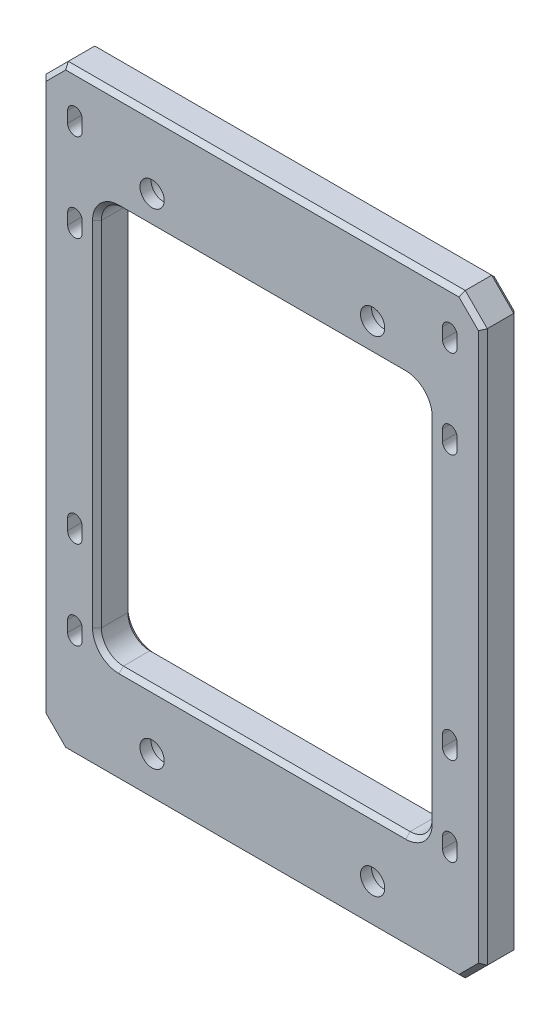
SolidWorks part; units mm, degrees
ref_plane "前视基准面" through (0, 0, 0) normal (0, 0, 1) x (1, 0, 0)
ref_plane "上视基准面" through (0, 0, 0) normal (0, 1, 0) x (1, 0, 0)
ref_plane "右视基准面" through (0, 0, 0) normal (1, 0, 0) x (0, 0, -1)
sketch "草图1" plane through (0, 0, 0) normal (0, 0, 1) x (1, 0, 0)
  line L1 (-100, 135) -> (100, 135)
  line L2 (-100, 135) -> (-100, -135)
  line L3 (-100, -135) -> (100, -135)
  line L4 (100, 135) -> (100, -135)
  line L5 (-100, 135) -> (100, -135) construction
  line L6 (-100, -135) -> (100, 135) construction
  point P0 (0, 0)
  dimension "D1" = 270
  dimension "D2" = 200
extrude "凸台-拉伸1" add sketch "草图1" along normal blind 16
hole_wizard "打孔尺寸(%根据)内六角圆柱头螺钉的类型1" positions "草图2" profile "草图3" counterbore size "M10" standard "GB" end condition through all
sketch "草图2" plane through (0, 0, 0) normal (0, 0, -1) x (-1, 0, 0)
  point P0 (-50, -116)
  point P2 (50, -116)
  point P4 (-50, 104)
  point P6 (50, 104)
sketch "草图3" plane through (50, -116, 0) normal (1, 0, 0) x (0, 1, 0)
  line L0 (0, 0) -> (0, 16)
  line L1 (0, 16) -> (5.5, 16)
  line L3 (5.5, 16) -> (5.5, 11)
  line L4 (5.5, 11) -> (9, 11)
  line L5 (9, 11) -> (9, 0)
  line L7 (9, 0) -> (0, 0)
  line L11 (0, -6.35) -> (0, 107.95) construction
  dimension "通孔孔直径" = 11
  dimension "通孔孔深度" = 16
  dimension "柱形沉头孔直径" = 18
  dimension "柱形沉头孔深度" = 11
sketch "草图4" plane through (0, 0, 16) normal (0, 0, 1) x (1, 0, 0)
  line L8 (100, -40.9) -> (-100, -40.9) construction
  line L9 (100, -80.9) -> (-100, -80.9) construction
  line L10 (100, -89.1) -> (-100, -89.1) construction
  line L11 (100, -49.1) -> (-100, -49.1) construction
  line L12 (100, 79.1) -> (-100, 79.1) construction
  line L13 (100, 70.9) -> (-100, 70.9) construction
  line L14 (100, 110.9) -> (-100, 110.9) construction
  line L15 (100, 119.1) -> (-100, 119.1) construction
  line L16 (100, -135) -> (100, 135) construction
  line L17 (-100, 135) -> (-100, -135) construction
  line L18 (100, -135) -> (100, 135) construction
  line L19 (-100, 135) -> (-100, -135) construction
  line L20 (0, 119.1) -> (0, 110.9) construction
  line L21 (0, 79.1) -> (0, 70.9) construction
  line L22 (0, -40.9) -> (0, -49.1) construction
  line L23 (0, -80.9) -> (0, -89.1) construction
  line L24 (-85, 115) -> (85, 115) construction
  line L25 (-85, 75) -> (85, 75) construction
  line L26 (-85, -45) -> (85, -45) construction
  line L27 (-85, -85) -> (85, -85) construction
  line L28 (-85, 112.5) -> (-85, 117.5) construction
  line L29 (-88.3, 112.5) -> (-88.3, 117.5)
  line L30 (-81.7, 112.5) -> (-81.7, 117.5)
  line L31 (85, 112.5) -> (85, 117.5) construction
  line L32 (81.7, 112.5) -> (81.7, 117.5)
  line L33 (88.3, 112.5) -> (88.3, 117.5)
  line L34 (85, 72.5) -> (85, 77.5) construction
  line L35 (81.7, 72.5) -> (81.7, 77.5)
  line L36 (88.3, 72.5) -> (88.3, 77.5)
  line L37 (-85, 72.5) -> (-85, 77.5) construction
  line L38 (-88.3, 72.5) -> (-88.3, 77.5)
  line L39 (-81.7, 72.5) -> (-81.7, 77.5)
  line L40 (-85, -47.5) -> (-85, -42.5) construction
  line L41 (-88.3, -47.5) -> (-88.3, -42.5)
  line L42 (-81.7, -47.5) -> (-81.7, -42.5)
  line L43 (-85, -87.5) -> (-85, -82.5) construction
  line L44 (-88.3, -87.5) -> (-88.3, -82.5)
  line L45 (-81.7, -87.5) -> (-81.7, -82.5)
  line L46 (85, -47.5) -> (85, -42.5) construction
  line L47 (81.7, -47.5) -> (81.7, -42.5)
  line L48 (88.3, -47.5) -> (88.3, -42.5)
  line L49 (85, -87.5) -> (85, -82.5) construction
  line L50 (81.7, -87.5) -> (81.7, -82.5)
  line L51 (88.3, -87.5) -> (88.3, -82.5)
  arc A0 (-88.3, 112.5) -> (-81.7, 112.5) centre (-85, 112.5) ccw
  arc A1 (-81.7, 117.5) -> (-88.3, 117.5) centre (-85, 117.5) ccw
  arc A2 (81.7, 112.5) -> (88.3, 112.5) centre (85, 112.5) ccw
  arc A3 (88.3, 117.5) -> (81.7, 117.5) centre (85, 117.5) ccw
  arc A4 (81.7, 72.5) -> (88.3, 72.5) centre (85, 72.5) ccw
  arc A5 (88.3, 77.5) -> (81.7, 77.5) centre (85, 77.5) ccw
  arc A6 (-88.3, 72.5) -> (-81.7, 72.5) centre (-85, 72.5) ccw
  arc A7 (-81.7, 77.5) -> (-88.3, 77.5) centre (-85, 77.5) ccw
  arc A8 (-88.3, -47.5) -> (-81.7, -47.5) centre (-85, -47.5) ccw
  arc A9 (-81.7, -42.5) -> (-88.3, -42.5) centre (-85, -42.5) ccw
  arc A10 (-88.3, -87.5) -> (-81.7, -87.5) centre (-85, -87.5) ccw
  arc A11 (-81.7, -82.5) -> (-88.3, -82.5) centre (-85, -82.5) ccw
  arc A12 (81.7, -47.5) -> (88.3, -47.5) centre (85, -47.5) ccw
  arc A13 (88.3, -42.5) -> (81.7, -42.5) centre (85, -42.5) ccw
  arc A14 (81.7, -87.5) -> (88.3, -87.5) centre (85, -87.5) ccw
  arc A15 (88.3, -82.5) -> (81.7, -82.5) centre (85, -82.5) ccw
  point P31 (0, 115)
  point P34 (0, 75)
  point P37 (0, -45)
  point P40 (0, -85)
  point P42 (-85, 115)
  point P48 (85, 115)
  point P55 (85, 75)
  point P62 (-85, 75)
  point P70 (-85, -45)
  point P76 (-85, -85)
  point P83 (85, -45)
  point P90 (85, -85)
  dimension "D1" = 170
  dimension "D2" = 6.6
  dimension "D3" = 5
extrude "切除-拉伸1" cut sketch "草图4" against normal through all
sketch "草图5" plane through (0, 0, 0) normal (0, 0, -1) x (-1, 0, 0)
  line L1 (75, -90) -> (-75, -90)
  line L2 (75, -90) -> (75, 90)
  line L3 (75, 90) -> (-75, 90)
  line L4 (-75, -90) -> (-75, 90)
  line L5 (75, -90) -> (-75, 90) construction
  line L6 (75, 90) -> (-75, -90) construction
  point P0 (0, 0)
  dimension "D1" = 150
  dimension "D2" = 180
extrude "切除-拉伸2" cut sketch "草图5" against normal through all
fillet "圆角1" radius 10 4 edges at (-75, 90, 8) (75, 90, 8) (-75, -90, 8) (75, -90, 8)
chamfer "倒角1" distance 10 angle 45 4 edges at (100, -135, 8) (100, 135, 8) (-100, 135, 8) (-100, -135, 8)
chamfer "倒角2" distance 2 angle 45 32 edges at (75, 0, 16) (72.0711, -87.0711, 16) (72.0711, 87.0711, 16) (0, -90, 16) (0, 90, 16) (-72.0711, -87.0711, 16) (-72.0711, 87.0711, 16) (-75, 0, 16) (75, 0, 0) (72.0711, -87.0711, 0) (72.0711, 87.0711, 0) (0, -90, 0) (0, 90, 0) (-72.0711, -87.0711, 0) (-72.0711, 87.0711, 0) (-75, 0, 0) (95, -130, 16) (0, -135, 16) (-95, -130, 16) (-100, 0, 16) (-95, 130, 16) (0, 135, 16) (100, 0, 16) (95, 130, 16) (95, 130, 0) (0, 135, 0) (-95, 130, 0) (-100, 0, 0) (-95, -130, 0) (0, -135, 0) (95, -130, 0) (100, 0, 0)
